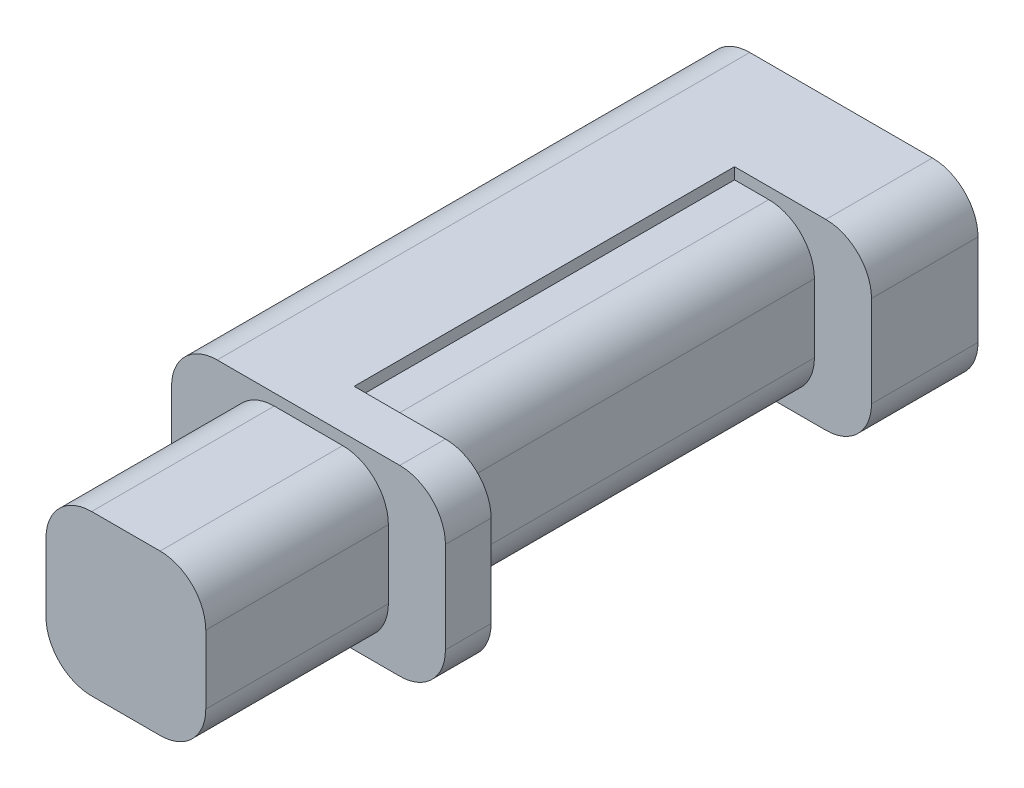
SolidWorks part; units mm, degrees
ref_plane "Front Plane" through (0, 0, 0) normal (0, 0, 1) x (1, 0, 0)
ref_plane "Top Plane" through (0, 0, 0) normal (0, 1, 0) x (1, 0, 0)
ref_plane "Right Plane" through (0, 0, 0) normal (1, 0, 0) x (0, 0, -1)
sketch "Sketch1" plane through (0, 0, 0) normal (0, 0, 1) x (1, 0, 0)
  line L0 (-2.25, 5.25) -> (2.25, 5.25)
  line L1 (5.25, 2.25) -> (5.25, -2.25)
  line L2 (2.25, -5.25) -> (-2.25, -5.25)
  line L3 (-5.25, -2.25) -> (-5.25, 2.25)
  line L4 (0, 5.25) -> (0, -5.25) construction
  line L5 (-5.25, 0) -> (5.25, 0) construction
  arc A0 (2.25, 5.25) -> (5.25, 2.25) centre (2.25, 2.25) cw
  arc A1 (5.25, -2.25) -> (2.25, -5.25) centre (2.25, -2.25) cw
  arc A2 (-2.25, -5.25) -> (-5.25, -2.25) centre (-2.25, -2.25) cw
  arc A3 (-5.25, 2.25) -> (-2.25, 5.25) centre (-2.25, 2.25) cw
  point P17 (0, 0)
  dimension "D2" = 3
  dimension "D3" = 3
  dimension "D4" = 3
  dimension "D5" = 3
  dimension "D1" = 4.5
extrude "Boss-Extrude1" add sketch "Sketch1" along normal blind 40
sketch "Sketch2" plane through (0, 0, 0) normal (0, 0, 1) x (1, 0, 0)
  line L16 (0.0004, 6) -> (-0.0004, -6) construction
  line L17 (9, -0.0008) -> (-9, 0.0008) construction
  line L24 (9, -3.0008) -> (9, 2.9992)
  line L25 (-6.0004, -5.9992) -> (5.9996, -6.0008)
  line L26 (-9, 3.0008) -> (-9, -2.9992)
  line L27 (6.0004, 5.9992) -> (-5.9996, 6.0008)
  arc A28 (5.9996, -6.0008) -> (9, -3.0008) centre (6, -3.0008) ccw
  arc A29 (-9, -2.9992) -> (-6.0004, -5.9992) centre (-6, -2.9992) ccw
  arc A30 (-5.9996, 6.0008) -> (-9, 3.0008) centre (-6, 3.0008) ccw
  arc A31 (9, 2.9992) -> (6.0004, 5.9992) centre (6, 2.9992) ccw
  dimension "D3" = 3
  dimension "D1" = 6
  dimension "D2" = 12
extrude "Boss-Extrude2" add sketch "Sketch2" against normal blind 7
sketch "Sketch3" plane through (0, 0, 0) normal (0, 0, 1) x (1, 0, 0)
  line L1 (-2.25, -5.25) -> (2.25, -5.25) construction
  line L4 (0.0004, 5.25) -> (-6, 5.25)
  line L5 (-8.2492, 3.0008) -> (-8.2492, -2.9992)
  line L6 (-6.0006, -5.2484) -> (0.0004, -5.25)
  line L7 (2.25, 5.25) -> (-2.25, 5.25) construction
  line L12 (0.0004, 5.25) -> (0.0004, 6)
  line L13 (6.0004, 5.9992) -> (-5.9996, 6.0008) construction
  line L14 (0.0004, -5.25) -> (0.0004, -6)
  line L17 (-6.0004, -5.9992) -> (5.9996, -6.0008) construction
  line L18 (-9, 3.0008) -> (-9, -2.9992) construction
  line L19 (-6.0004, -5.9992) -> (0.0004, -6)
  line L20 (-9, 3.0008) -> (-9, -2.9992)
  line L21 (0.0004, 6) -> (-5.9996, 6.0008)
  arc A1 (-6, 5.25) -> (-8.2492, 3.0008) centre (-6, 3.0008) ccw
  arc A2 (-9, -2.9992) -> (-6.0004, -5.9992) centre (-6, -2.9992) ccw construction
  arc A3 (-5.9996, 6.0008) -> (-9, 3.0008) centre (-6, 3.0008) ccw construction
  arc A4 (-8.2492, -2.9992) -> (-6.0006, -5.2484) centre (-6, -2.9992) ccw
  arc A12 (-9, -2.9992) -> (-6.0004, -5.9992) centre (-6, -2.9992) ccw
  arc A13 (-5.9996, 6.0008) -> (-9, 3.0008) centre (-6, 3.0008) ccw
  point P11 (-6.3821, -5.25)
  point P12 (1.7164, -5.25)
  point P13 (0, 0)
extrude "Boss-Extrude3" add sketch "Sketch3" along normal blind 25
sketch "Sketch5" plane through (0, 0, 40) normal (0, 0, 1) x (1, 0, 0)
  line L0 (0.0004, -6) -> (5.9996, -6.0008) construction
  line L1 (0.0004, -6) -> (5.9996, -6.0008)
  line L2 (9, -3.0008) -> (9, 2.9992) construction
  line L3 (6.0004, 5.9992) -> (0.0004, 6) construction
  line L12 (-6.0004, -5.9992) -> (0.0004, -6) construction
  line L13 (-9, 3.0008) -> (-9, -2.9992) construction
  line L14 (9, -3.0008) -> (9, 2.9992)
  line L15 (6.0004, 5.9992) -> (0.0004, 6)
  line L16 (-6.0004, -5.9992) -> (0.0004, -6)
  line L17 (-9, 3.0008) -> (-9, -2.9992)
  line L18 (0.0004, 6) -> (-5.9996, 6.0008) construction
  line L19 (0.0004, 6) -> (-5.9996, 6.0008)
  arc A0 (5.9996, -6.0008) -> (9, -3.0008) centre (6, -3.0008) ccw construction
  arc A1 (9, 2.9992) -> (6.0004, 5.9992) centre (6, 2.9992) ccw construction
  arc A2 (-9, -2.9992) -> (-6.0004, -5.9992) centre (-6, -2.9992) ccw construction
  arc A3 (-5.9996, 6.0008) -> (-9, 3.0008) centre (-6, 3.0008) ccw construction
  arc A12 (5.9996, -6.0008) -> (9, -3.0008) centre (6, -3.0008) ccw
  arc A13 (9, 2.9992) -> (6.0004, 5.9992) centre (6, 2.9992) ccw
  arc A14 (-9, -2.9992) -> (-6.0004, -5.9992) centre (-6, -2.9992) ccw
  arc A15 (-5.9996, 6.0008) -> (-9, 3.0008) centre (-6, 3.0008) ccw
extrude "Boss-Extrude4" add sketch "Sketch5" along normal blind 3 from offset 15
